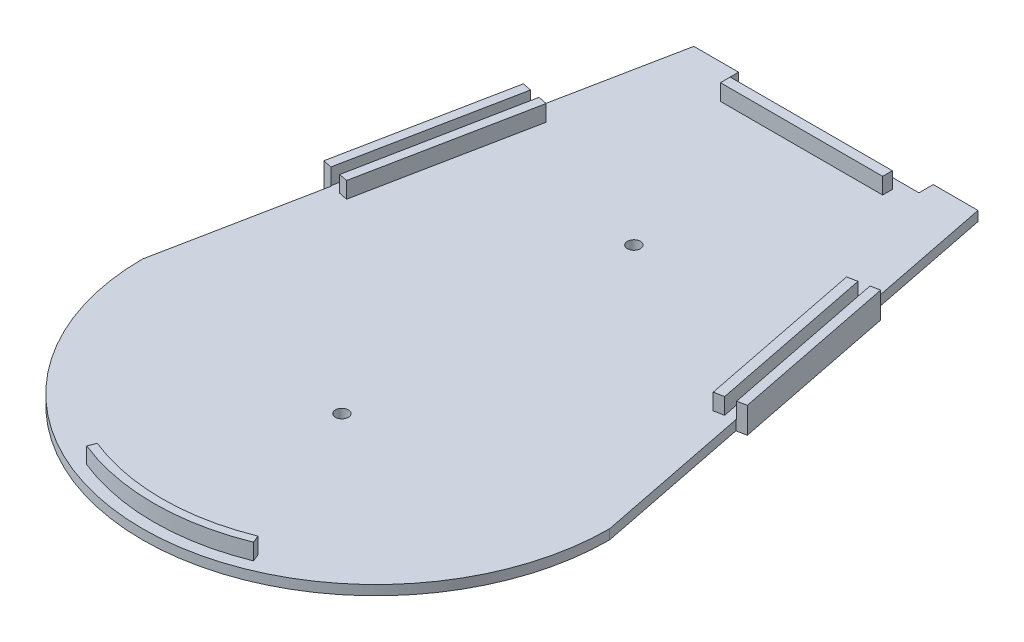
SolidWorks part; units mm, degrees
ref_plane "Alzado" through (0, 0, 0) normal (0, 0, 1) x (1, 0, 0)
ref_plane "Planta" through (0, 0, 0) normal (0, 1, 0) x (1, 0, 0)
ref_plane "Vista lateral" through (0, 0, 0) normal (1, 0, 0) x (0, 0, -1)
sketch "Croquis1" plane through (0, 0, 0) normal (0, 0, 1) x (1, 0, 0)
  line L0 (-72.0002, 10.9851) -> (-43.7984, 152.7307)
  line L1 (-43.7984, 152.7307) -> (-30.0002, 152.7307)
  line L2 (-30.0002, 152.7307) -> (-30.0002, 148.3307)
  line L3 (-30.0002, 148.3307) -> (29.9998, 148.3307)
  line L4 (29.9998, 148.3307) -> (29.9998, 152.7307)
  line L5 (29.9998, 152.7307) -> (43.7981, 152.7307)
  line L6 (43.7981, 152.7307) -> (71.9998, 10.9851)
  circle A0 centre (-0.0002, 10.9851) radius 72
sketch "Croquis2" plane through (0, 0, 0) normal (0, 1, 0) x (1, 0, 0)
  line L0 (-72, -34.8728) -> (-43.7983, 106.8728)
  line L1 (-43.7983, 106.8728) -> (-30, 106.8728)
  line L2 (-30, 106.8728) -> (-30, 102.4728)
  line L3 (-30, 102.4728) -> (30, 102.4728)
  line L4 (30, 102.4728) -> (30, 106.8728)
  line L5 (30, 106.8728) -> (43.7983, 106.8728)
  line L6 (43.7983, 106.8728) -> (72, -34.8728)
  circle A0 centre (0, -34.8728) radius 72
extrude "Saliente-Extruir1" add sketch "Croquis2" along normal blind 3 contours L6 A0 L0 | A0 L6 L5 L4 L3 L2 L1 L0
sketch "Croquis3" plane through (0, 3, 0) normal (0, 1, 0) x (1, 0, 0)
  line L0 (0, -106.8728) -> (0, -86.8225)
  line L1 (24.7617, -96.0518) -> (25.6996, -98.3691)
  line L2 (-24.7617, -96.0518) -> (-25.6996, -98.3691)
  line L4 (0, 102.4728) -> (0, 34.1272)
  circle A0 centre (0, -34.8728) radius 69
  circle A1 centre (0, -34.8728) radius 66
  circle A2 centre (0, -34.8728) radius 68.5
  arc A3 (-72, -34.8728) -> (72, -34.8728) centre (0, -34.8728) ccw construction
  point P18 (0, 102.4728)
  dimension "D1" = 138
  dimension "D2" = 132
  dimension "D3" = 137
extrude "Saliente-Extruir3" add sketch "Croquis3" along normal blind 5 contours L0 A2 L1 A1 | L2 A2 L0 A1
sketch "Croquis5" plane through (0, 3, 0) normal (0, 1, 0) x (1, 0, 0)
  line L0 (0, 102.4728) -> (0, 99.2728)
  line L1 (-30, 102.4728) -> (30, 102.4728) construction
  line L2 (-25, 99.2728) -> (25, 99.2728)
  line L4 (-25, 99.2728) -> (25, 99.2728)
  line L5 (-25, 99.2728) -> (-25, 96.2728)
  line L6 (-25, 96.2728) -> (25, 96.2728)
  line L7 (25, 99.2728) -> (25, 96.2728)
  point P8 (0, 99.2728)
  dimension "D1" = 3.2
  dimension "D2" = 50
  dimension "D3" = 3
extrude "Saliente-Extruir4" add sketch "Croquis5" along normal blind 5 contours L7 L2 L5 L6
sketch "Croquis6" plane through (0, 3, 0) normal (0, 1, 0) x (1, 0, 0)
  line L0 (-72, -34.8728) -> (-69, -34.8728)
  line L1 (-43.7983, 106.8728) -> (-40.7983, 106.8728)
  line L2 (-43.7983, 106.8728) -> (-30, 106.8728) construction
  line L3 (-40.7983, 106.8728) -> (-69, -34.8728)
  line L4 (-0.0002, 0) -> (-0.0002, 66.4982)
  line L5 (-72.0002, 0) -> (71.9998, 0) construction
  line L6 (-59.4502, 13.1259) -> (-56.5078, 12.5405)
  line L7 (-59.4502, 13.1259) -> (-49.2406, 64.4405)
  line L8 (-56.5078, 12.5405) -> (-46.2983, 63.855)
  line L9 (-49.2406, 64.4405) -> (-46.2983, 63.855)
  line L10 (56.5075, 12.5405) -> (46.298, 63.855)
  line L11 (49.2403, 64.4405) -> (46.298, 63.855)
  line L12 (59.4499, 13.1259) -> (49.2403, 64.4405)
  line L13 (59.4499, 13.1259) -> (56.5075, 12.5405)
  line L14 (-49.2406, 64.4405) -> (-49.0445, 64.4014)
  line L15 (-49.0445, 64.4014) -> (-59.1641, 13.069)
  line L16 (-49.0445, 64.4014) -> (-49.3292, 64.4576)
  line L17 (-59.1641, 13.069) -> (-59.4488, 13.1251)
  line L18 (-49.3292, 64.4576) -> (-59.4488, 13.1251)
  line L19 (59.1638, 13.069) -> (59.4485, 13.1251)
  line L20 (49.3289, 64.4576) -> (59.4485, 13.1251)
  line L21 (49.0442, 64.4014) -> (49.3289, 64.4576)
  line L22 (49.0442, 64.4014) -> (59.1638, 13.069)
  dimension "D1" = 3
  dimension "D2" = 3
  dimension "D3" = 3
  dimension "D4" = 0.2
extrude "Saliente-Extruir6" add sketch "Croquis6" along normal blind 5 contours L9 L15 L6 L8 | L10 L11 L12 L13
sketch "Croquis8" plane through (0, 3, 0) normal (0, 1, 0) x (1, 0, 0)
  line L0 (-56.5078, 12.5405) -> (-62.3359, 13.7001)
  line L1 (-72, -34.8728) -> (-43.7983, 106.8728) construction
  line L2 (-62.3359, 13.7001) -> (-65.2783, 14.2855)
  line L3 (-46.2983, 63.855) -> (-52.1264, 65.0146)
  line L4 (-52.1264, 65.0146) -> (-55.0687, 65.6)
  line L5 (-55.0687, 65.6) -> (-65.2783, 14.2855)
  line L6 (-62.3359, 13.7001) -> (-52.1264, 65.0146)
  line L7 (59.4499, 13.1259) -> (62.3359, 13.7001)
  line L8 (43.7983, 106.8728) -> (72, -34.8728) construction
  line L9 (62.3359, 13.7001) -> (65.278, 14.2855)
  line L10 (46.298, 63.855) -> (49.2403, 64.4405)
  line L11 (49.2403, 64.4405) -> (52.1264, 65.0147)
  line L12 (52.1264, 65.0147) -> (55.0684, 65.6)
  line L13 (55.0684, 65.6) -> (65.278, 14.2855)
  line L14 (52.1264, 65.0147) -> (62.3359, 13.7001)
  line M18 (72, -34.8728) -> (43.7983, 106.8728)
  line M24 (-43.7983, 106.8728) -> (-72, -34.8728)
extrude "Saliente-Extruir7" add sketch "Croquis8" along normal blind 5 and the other way blind 3 contours L4 L5 L2 M24 | L13 L12 L9 M18
sketch "Croquis9" plane through (0, 8, 0) normal (0, 1, 0) x (1, 0, 0)
  line L0 (-62.3359, 13.7001) -> (-62.5321, 13.7391)
  line L1 (-62.3359, 13.7001) -> (-65.2783, 14.2855) construction
  line L2 (-52.1264, 65.0146) -> (-62.3359, 13.7001)
  line L3 (-52.1264, 65.0146) -> (-52.3226, 65.0536)
  line L4 (-62.3359, 13.7001) -> (-62.5321, 13.7391)
  line L5 (-52.3226, 65.0536) -> (-62.5321, 13.7391)
  line L6 (46.298, 63.855) -> (46.4942, 63.8941)
  line L7 (49.2403, 64.4405) -> (46.298, 63.855) construction
  line L8 (56.5075, 12.5405) -> (46.298, 63.855)
  line L9 (56.5075, 12.5405) -> (56.7037, 12.5796)
  line L10 (46.298, 63.855) -> (46.4942, 63.8941)
  line L11 (56.7037, 12.5796) -> (46.4942, 63.8941)
  line L12 (52.1264, 65.0147) -> (52.3225, 65.0537)
  line L13 (52.1264, 65.0147) -> (55.0684, 65.6) construction
  line L14 (62.3359, 13.7001) -> (52.1264, 65.0147)
  line L15 (62.3359, 13.7001) -> (62.5321, 13.7392)
  line L16 (52.1264, 65.0147) -> (52.3225, 65.0537)
  line L17 (62.5321, 13.7392) -> (52.3225, 65.0537)
  line M11 (-52.1264, 65.0146) -> (-55.0687, 65.6)
  line M13 (-65.2783, 14.2855) -> (-62.3359, 13.7001)
  line M14 (-62.3359, 13.7001) -> (-52.1264, 65.0146)
extrude "Cortar-Extruir2" cut sketch "Croquis9" against normal blind 5 contours L15 L17 L12 L14 | L5 M11 M13 M14
sketch "Croquis11" plane through (0, 3, 0) normal (0, 1, 0) x (1, 0, 0)
  line L0 (-0.0002, 44.5907) -> (-0.0002, -45.4093)
  circle A0 centre (-0.0002, 44.5907) radius 2
  circle A1 centre (-0.0002, -45.4093) radius 2
  point P3 (-0.0002, -0.4093)
  dimension "D1" = 4
  dimension "D2" = 4
extrude "Cortar-Extruir3" cut sketch "Croquis11" against normal blind 5
